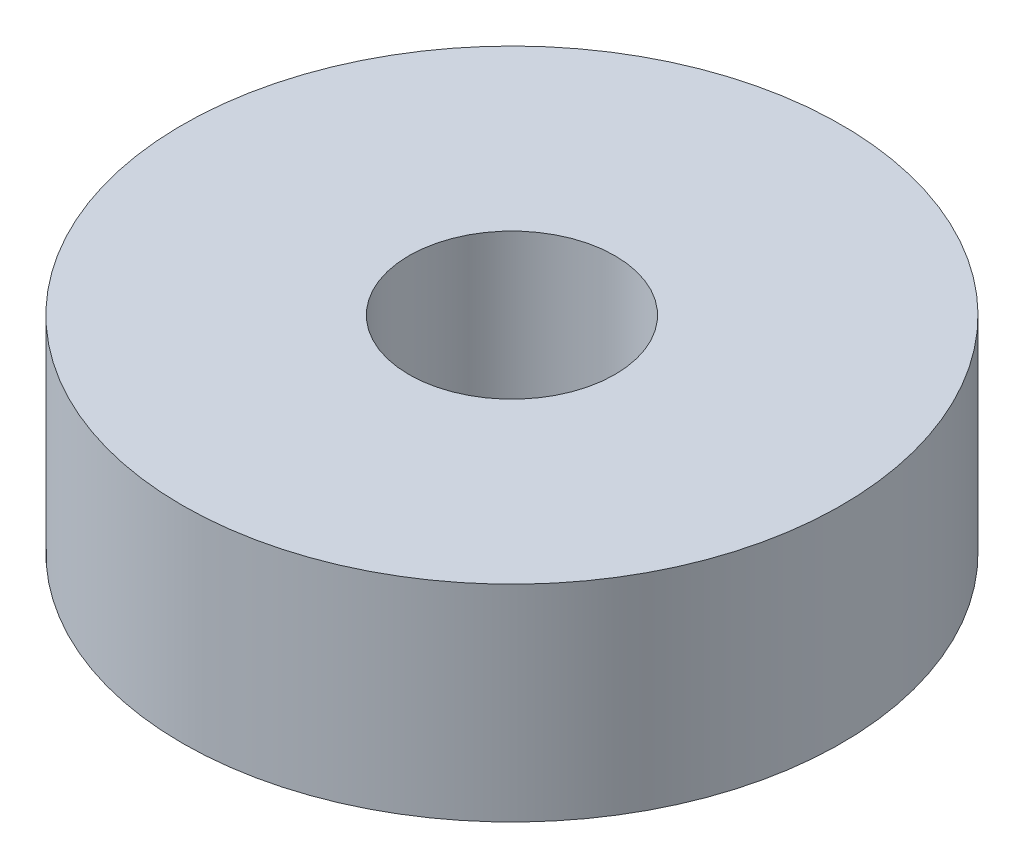
SolidWorks part; units mm, degrees
ref_plane "Front Plane" through (0, 0, 0) normal (0, 0, 1) x (1, 0, 0)
ref_plane "Top Plane" through (0, 0, 0) normal (0, 1, 0) x (1, 0, 0)
ref_plane "Right Plane" through (0, 0, 0) normal (1, 0, 0) x (0, 0, -1)
sketch "Sketch1" plane through (0, 0, 0) normal (0, 1, 0) x (1, 0, 0)
  circle A0 centre (0, 0) radius 8
  circle A1 centre (0, 0) radius 2.5
  dimension "D1" = 16
  dimension "D2" = 5
extrude "Boss-Extrude1" add sketch "Sketch1" along normal blind 5
